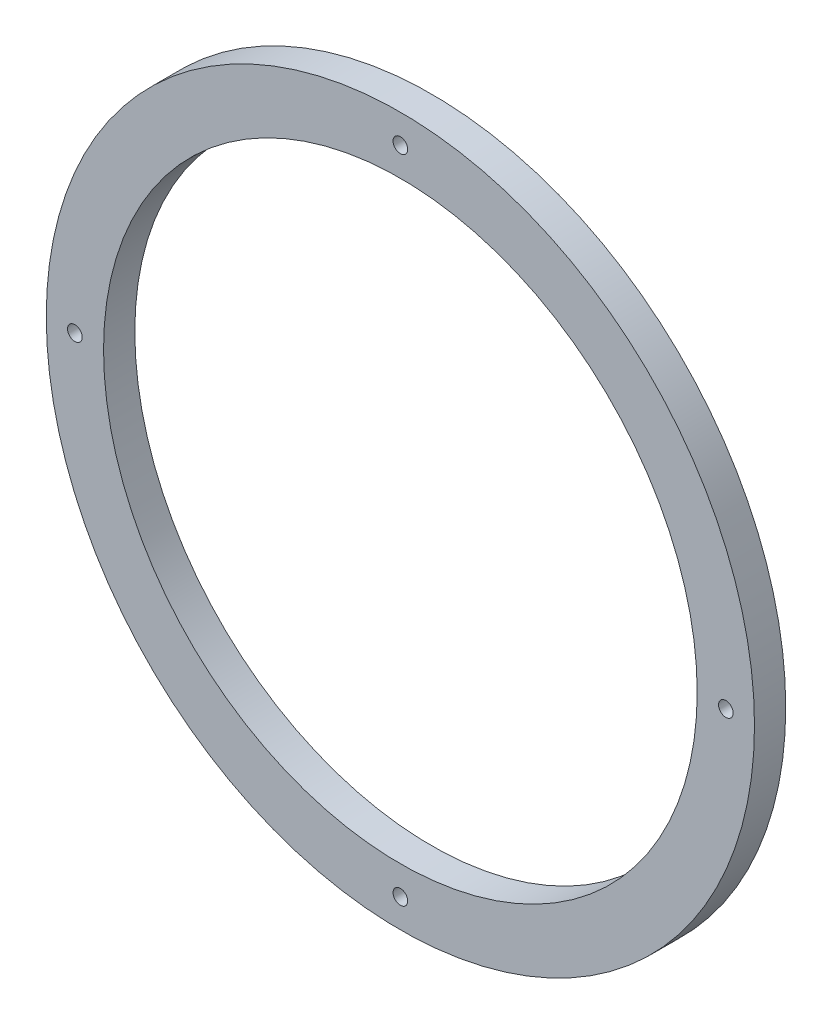
SolidWorks part; units mm, degrees
material "6061 Alloy"
ref_plane "Front Plane" through (0, 0, 0) normal (0, 0, 1) x (1, 0, 0)
ref_plane "Top Plane" through (0, 0, 0) normal (0, 1, 0) x (1, 0, 0)
ref_plane "Right Plane" through (0, 0, 0) normal (1, 0, 0) x (0, 0, -1)
sketch "Sketch1" plane through (0, 0, 0) normal (0, 0, 1) x (1, 0, 0)
  line L0 (0, 79.375) -> (0, 0) construction
  line L1 (0, 0) -> (-79.375, 0) construction
  circle A0 centre (0, 0) radius 72.39
  circle A1 centre (0, 0) radius 86.36
  circle A2 centre (0, 79.375) radius 1.7859
  circle A3 centre (79.375, 0) radius 1.7859
  circle A4 centre (0, -79.375) radius 1.7859
  circle A5 centre (-79.375, 0) radius 1.7859
  point P16 (0, 0)
  dimension "D1" = 144.78
  dimension "D4" = 3.5719
  dimension "D3" = 79.375
  dimension "D6" = 79.375
  dimension "D2" = 13.97
  dimension "D5" = 4
extrude "Boss-Extrude1" add sketch "Sketch1" along normal blind 7.62
